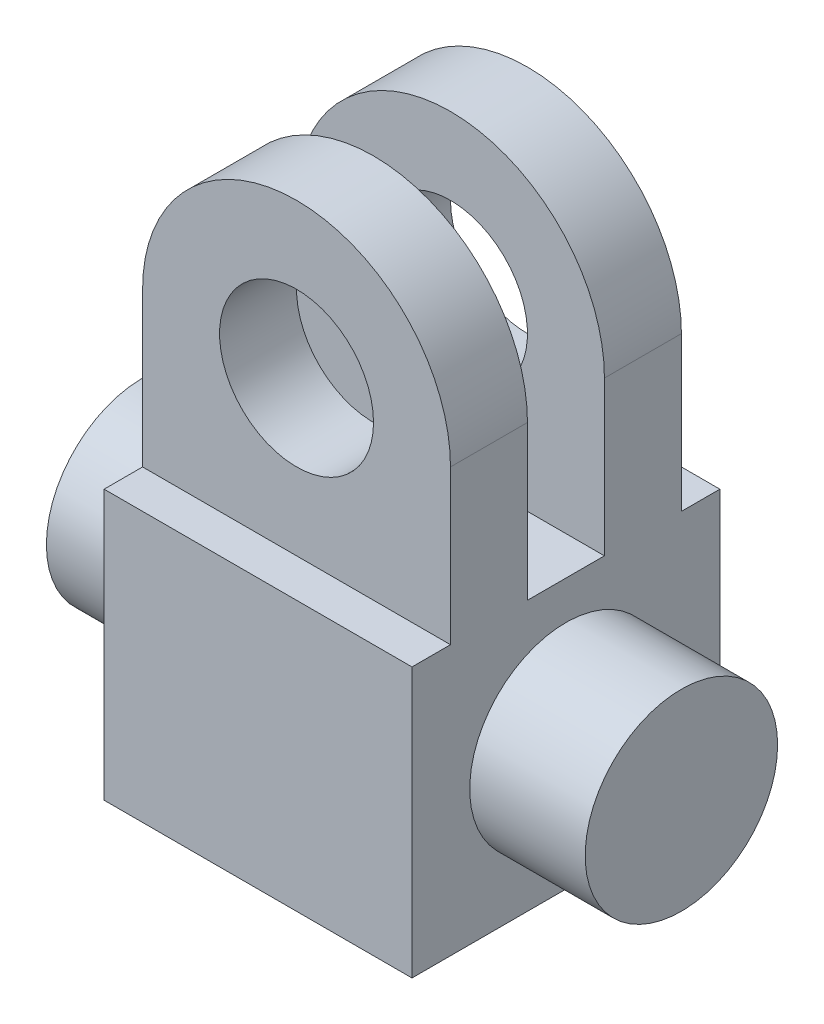
SolidWorks part; units mm, degrees
ref_plane "Alzado" through (0, 0, 0) normal (0, 0, 1) x (1, 0, 0)
ref_plane "Planta" through (0, 0, 0) normal (0, 1, 0) x (1, 0, 0)
ref_plane "Vista lateral" through (0, 0, 0) normal (1, 0, 0) x (0, 0, -1)
sketch "Croquis1" plane through (0, 0, 0) normal (0, 0, 1) x (1, 0, 0)
  line L0 (0, 0) -> (40, 0)
  line L1 (40, 0) -> (40, 70)
  line L2 (40, 70) -> (-40, 70)
  line L3 (-40, 70) -> (-40, 0)
  line L4 (-40, 0) -> (0, 0)
  point P3 (0, 70)
  dimension "D1" = 80
  dimension "D2" = 70
extrude "Saliente-Extruir1" add sketch "Croquis1" against normal blind 80
sketch "Croquis2" plane through (40, 0, 0) normal (1, 0, 0) x (0, 0, -1)
  line L0 (80, 0) -> (0, 0) construction
  circle A0 centre (40, 35) radius 25
  point P2 (0, 0)
  point P5 (0, 0)
  point P9 (40, 0)
  dimension "D3" = 50
  dimension "D1" = 80
  dimension "D2" = 35
extrude "Saliente-Extruir2" add sketch "Croquis2" along normal blind 30
sketch "Croquis3" plane through (-40, 0, 0) normal (-1, 0, 0) x (0, 0, 1)
  line L0 (-80, 0) -> (0, 0) construction
  circle A0 centre (-40, 35) radius 25
  point P4 (-40, 0)
  dimension "D1" = 50
  dimension "D2" = 35
extrude "Saliente-Extruir3" add sketch "Croquis3" along normal blind 30
ref_plane "Plano1" through (0, 0, -10) normal (0, 0, 1) x (1, 0, 0)
sketch "Croquis4" plane through (0, 0, -10) normal (0, 0, 1) x (1, 0, 0)
  line L0 (40, 70) -> (-40, 70) construction
  line L1 (-40, 110) -> (-40, 70)
  line L2 (40, 110) -> (40, 70)
  line L3 (-40, 70) -> (0, 70)
  line L4 (0, 70) -> (40, 70)
  circle A0 centre (0, 110) radius 20
  arc A1 (40, 110) -> (-40, 110) centre (0, 110) ccw
  point P5 (0, 70)
  point P10 (40, 70)
  point P12 (40, 70)
  dimension "D1" = 40
  dimension "D2" = 80
  dimension "D3" = 40
  dimension "D4" = 40
  dimension "D5" = 40
extrude "Saliente-Extruir5" add sketch "Croquis4" against normal blind 20
ref_plane "Plano2" through (0, 0, -70) normal (0, 0, -1) x (-1, 0, 0)
sketch "Croquis5" plane through (0, 0, -70) normal (0, 0, -1) x (-1, 0, 0)
  line L0 (-40, 110) -> (-40, 70)
  line L1 (-40, 70) -> (40, 70)
  line L2 (40, 70) -> (40, 110)
  circle A0 centre (0, 110) radius 20
  arc A1 (40, 110) -> (-40, 110) centre (0, 110) ccw
  dimension "D1" = 40
extrude "Saliente-Extruir6" add sketch "Croquis5" against normal blind 20
